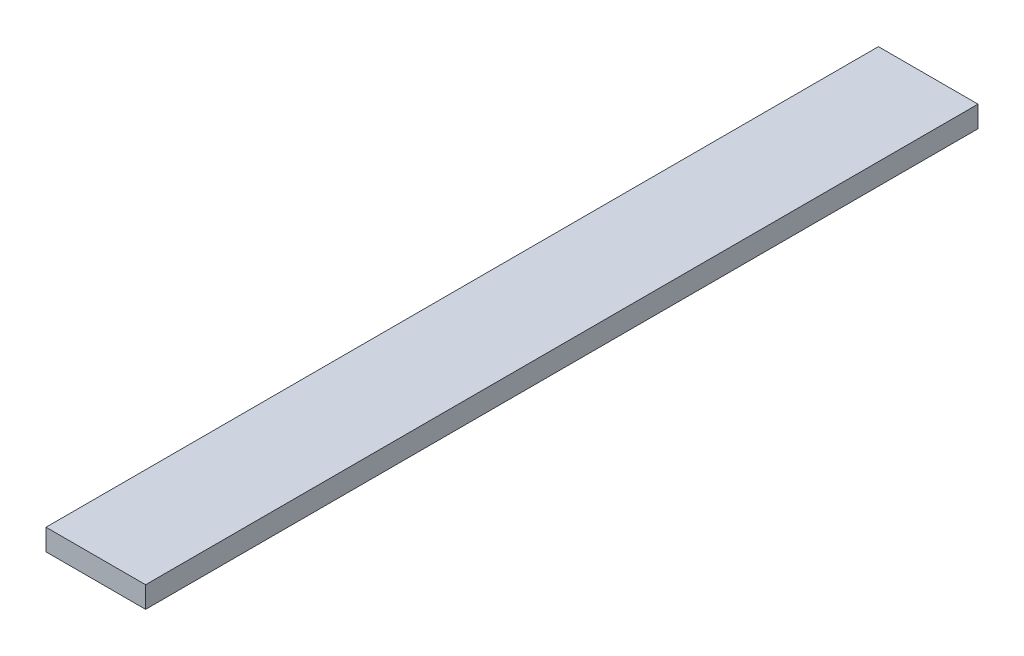
SolidWorks part; units mm, degrees
ref_plane "Plano frontal" through (0, 0, 0) normal (0, 0, 1) x (1, 0, 0)
ref_plane "Plano superior" through (0, 0, 0) normal (0, 1, 0) x (1, 0, 0)
ref_plane "Plano direito" through (0, 0, 0) normal (1, 0, 0) x (0, 0, -1)
sketch "Esboço1" plane through (0, 0, 0) normal (0, 0, 1) x (1, 0, 0)
  line L1 (35, 7.5) -> (-35, 7.5)
  line L2 (35, 7.5) -> (35, -7.5)
  line L3 (35, -7.5) -> (-35, -7.5)
  line L4 (-35, 7.5) -> (-35, -7.5)
  line L5 (35, 7.5) -> (-35, -7.5) construction
  line L6 (35, -7.5) -> (-35, 7.5) construction
  point P0 (0, 0)
  dimension "D1" = 70
  dimension "D2" = 15
extrude "Ressalto-extrusão1" add sketch "Esboço1" along normal blind 585
sketch "Esboço2" plane through (0, 7.5, 0) normal (0, 1, 0) x (1, 0, 0)
  line L0 (-35, -292.5) -> (35, -292.5) construction
  line L1 (-35, -585) -> (-35, 0) construction
  line L2 (35, -585) -> (35, 0) construction
  line L3 (0, -585) -> (0, 0) construction
  line L4 (35, -585) -> (-35, -585) construction
  line L5 (-35, -535) -> (35, -535) construction
  line L6 (-35, -50) -> (35, -50) construction
  line L7 (35, 0) -> (-35, 0) construction
  dimension "D1" = 50
  dimension "D2" = 50
sketch "Esboço3" plane through (0, 7.5, 0) normal (0, 1, 0) x (1, 0, 0)
  line L0 (-35, -50) -> (35, -50) construction
  line L1 (35, -585) -> (35, 0) construction
  line L2 (-35, -585) -> (-35, 0) construction
  line L3 (-33.7, -50) -> (-35, -50) construction
  line L4 (35, 0) -> (-35, 0) construction
  line L5 (-20, -50) -> (-20, -80.9365) construction
  dimension "D1" = 50
  dimension "D2" = 15
